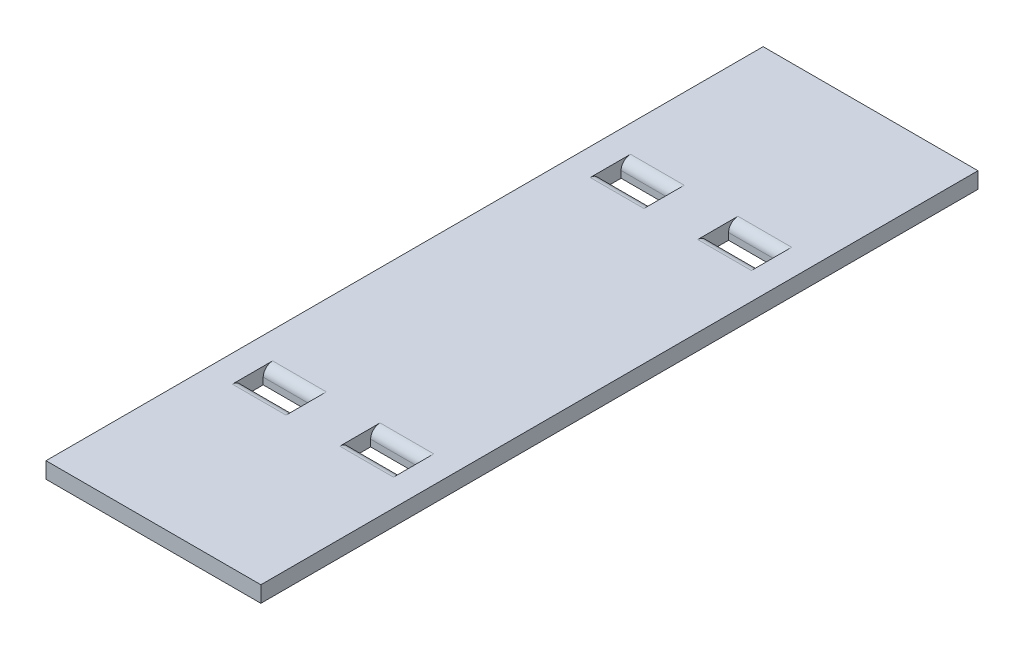
SolidWorks part; units mm, degrees
ref_plane "Front Plane" through (0, 0, 0) normal (0, 0, 1) x (1, 0, 0)
ref_plane "Top Plane" through (0, 0, 0) normal (0, 1, 0) x (1, 0, 0)
ref_plane "Right Plane" through (0, 0, 0) normal (1, 0, 0) x (0, 0, -1)
sketch "Sketch1" plane through (0, 0, 0) normal (0, 1, 0) x (1, 0, 0)
  line L1 (-20, 66.75) -> (20, 66.75)
  line L2 (-20, 66.75) -> (-20, -66.75)
  line L3 (-20, -66.75) -> (20, -66.75)
  line L4 (20, 66.75) -> (20, -66.75)
  line L5 (-20, 66.75) -> (20, -66.75) construction
  line L6 (-20, -66.75) -> (20, 66.75) construction
  point P0 (0, 0)
  dimension "D1" = 40
  dimension "D2" = 133.5
extrude "Boss-Extrude1" add sketch "Sketch1" along normal blind 3
sketch "Sketch2" plane through (0, 0, 0) normal (0, -1, 0) x (1, 0, 0)
  line L0 (0, 66.75) -> (0, 56.75) construction
  line L1 (-20, 66.75) -> (20, 66.75) construction
  line L2 (0, -1.65) -> (0, 1.65) construction
  line L3 (0, 56.75) -> (10, 56.75) construction
  line L4 (1.65, 0) -> (-1.65, 0) construction
  circle A0 centre (10, 56.75) radius 6.11
  circle A1 centre (-10, 56.75) radius 6.11
  circle A2 centre (-10, -56.75) radius 6.11
  circle A3 centre (10, -56.75) radius 6.11
  dimension "D3" = 12.22
  dimension "D1" = 10
  dimension "D2" = 10
extrude "Boss-Extrude2" add sketch "Sketch2" along normal blind 3
sketch "Sketch3" plane through (0, 3, 0) normal (0, 1, 0) x (1, 0, 0)
  line L0 (0, 66.75) -> (0, 33.3125) construction
  line L1 (0, -3.3) -> (0, 3.3) construction
  line L2 (0, 33.3125) -> (10, 33.3125) construction
  line L3 (20, -66.75) -> (20, 66.75) construction
  line L4 (5, 35.3125) -> (15, 35.3125)
  line L5 (5, 35.3125) -> (5, 31.3125)
  line L6 (5, 31.3125) -> (15, 31.3125)
  line L7 (15, 35.3125) -> (15, 31.3125)
  line L8 (5, 35.3125) -> (15, 31.3125) construction
  line L9 (5, 31.3125) -> (15, 35.3125) construction
  line L10 (20, 66.75) -> (-20, 66.75) construction
  line L11 (-5, 31.3125) -> (-15, 31.3125)
  line L12 (-15, 35.3125) -> (-15, 31.3125)
  line L13 (-5, 35.3125) -> (-15, 35.3125)
  line L14 (-5, 35.3125) -> (-5, 31.3125)
  line L16 (-3.3, 0) -> (3.3, 0) construction
  line L17 (-5, -35.3125) -> (-5, -31.3125)
  line L18 (-5, -35.3125) -> (-15, -35.3125)
  line L19 (-15, -35.3125) -> (-15, -31.3125)
  line L20 (-5, -31.3125) -> (-15, -31.3125)
  line L21 (5, -31.3125) -> (15, -31.3125)
  line L22 (15, -35.3125) -> (15, -31.3125)
  line L23 (5, -35.3125) -> (15, -35.3125)
  line L24 (5, -35.3125) -> (5, -31.3125)
  point P17 (0, 66.75)
  dimension "D1" = 33.4375
  dimension "D2" = 10
  dimension "D3" = 10
  dimension "D4" = 4
extrude "Cut-Extrude1" cut sketch "Sketch3" against normal up to next
fillet "Fillet2" radius 1.75 8 edges at (10, 3, -35.3125) (10, 3, -31.3125) (-10, 3, -35.3125) (-10, 3, -31.3125) (-10, 3, 35.3125) (-10, 3, 31.3125) (10, 3, 35.3125) (10, 3, 31.3125)
fillet "Fillet3" radius 1 4 edges at (-10, -3, 62.86) (10, -3, 50.64) (-10, -3, -62.86) (10, -3, -50.64)
